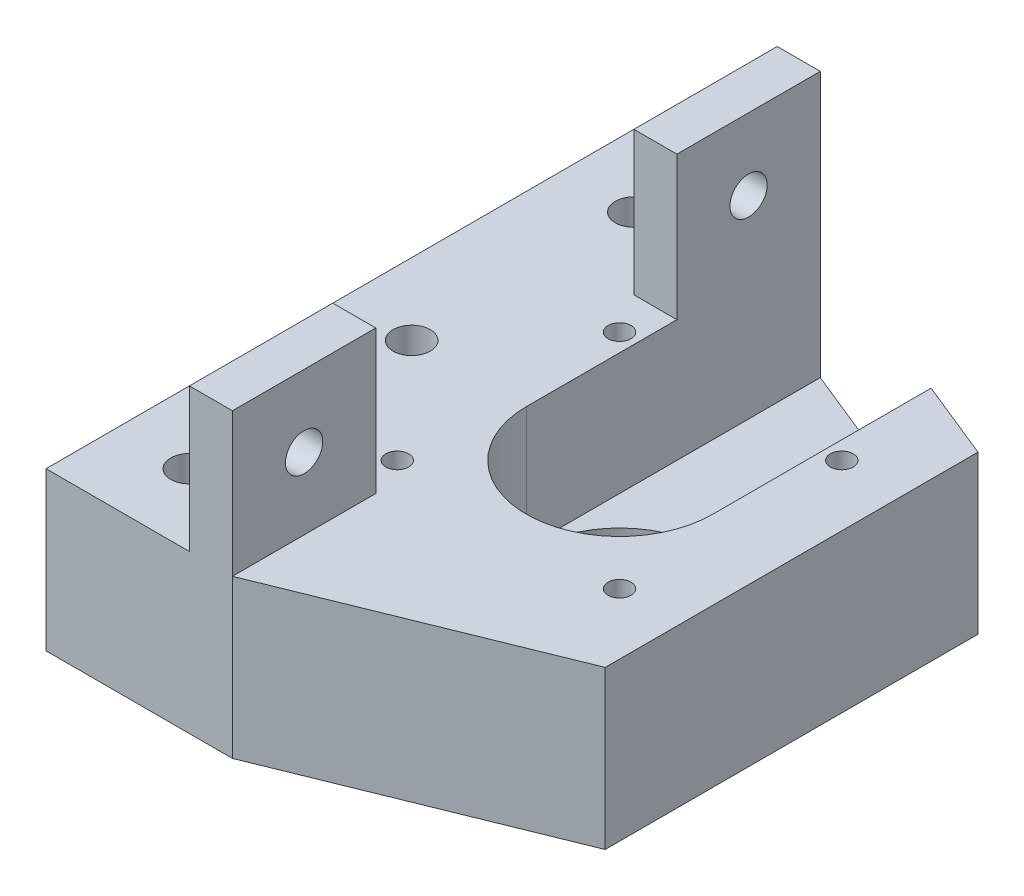
SolidWorks part; units mm, degrees
material "ABS"
ref_plane "Front Plane" through (0, 0, 0) normal (0, 0, 1) x (1, 0, 0)
ref_plane "Top Plane" through (0, 0, 0) normal (0, 1, 0) x (1, 0, 0)
ref_plane "Right Plane" through (0, 0, 0) normal (1, 0, 0) x (0, 0, -1)
sketch "Sketch1" plane through (0, 0, 0) normal (0, 1, 0) x (1, 0, 0)
  line L0 (0, 0) -> (0, 82)
  line L1 (0, 82) -> (26, 82)
  line L2 (26, 82) -> (63, 67)
  line L3 (63, 67) -> (63, 15)
  line L4 (63, 15) -> (26, 0)
  line L5 (26, 0) -> (0, 0)
  line L6 (0, 41) -> (63, 41) construction
  line L7 (26, 82) -> (26, 0) construction
  dimension "D1" = 82
  dimension "D2" = 26
  dimension "D3" = 15
  dimension "D4" = 37
extrude "Boss-Extrude1" add sketch "Sketch1" along normal blind 42
sketch "Sketch2" plane through (0, 0, 0) normal (0, 0, 1) x (1, 0, 0)
  line L0 (0, 42) -> (26, 42) construction
  line L1 (0, 42) -> (20, 42)
  line L2 (0, 42) -> (0, 22)
  line L3 (0, 22) -> (20, 22)
  line L4 (20, 42) -> (20, 22)
  line L5 (0, 42) -> (0, 0) construction
  dimension "D1" = 20
extrude "Cut-Extrude1" cut sketch "Sketch2" against normal through all
sketch "Sketch3" plane through (0, 42, 0) normal (0, 1, 0) x (1, 0, 0)
  line L0 (26, 82) -> (26, 62)
  line L1 (26, 62) -> (20, 62)
  line L2 (20, 82) -> (20, 0) construction
  line L3 (20, 62) -> (20, 20)
  line L4 (20, 20) -> (26, 20)
  line L5 (26, 20) -> (26, 0)
  line L6 (26, 0) -> (63, 15)
  line L7 (63, 15) -> (63, 67)
  line L8 (63, 67) -> (26, 82)
  dimension "D1" = 20
extrude "Cut-Extrude2" cut sketch "Sketch3" against normal offset from surface (37 mm away) 5 up to face at (29.6667, 0, -41)
sketch "Sketch6" plane through (0, 22, 0) normal (0, 1, 0) x (1, 0, 0)
  line L0 (10, 82) -> (10, 72) construction
  line L1 (0, 82) -> (20, 82) construction
  line L2 (10, 72) -> (10, 10) construction
  line L3 (10, 10) -> (10, 0) construction
  line L4 (0, 0) -> (20, 0) construction
  circle A0 centre (10, 72) radius 2.6
  circle A1 centre (10, 41) radius 2.6
  circle A2 centre (10, 10) radius 2.6
  dimension "D1" = 5.2
  dimension "D2" = 10
extrude "Cut-Extrude4" cut sketch "Sketch6" against normal through all
sketch "Sketch5" plane through (20, 0, 0) normal (-1, 0, 0) x (0, 0, 1)
  line L0 (-72, 32) -> (-10, 32) construction
  line L1 (-62, 22) -> (-20, 22) construction
  line L2 (-82, 22) -> (-82, 42) construction
  line L3 (0, 22) -> (0, 42) construction
  circle A0 centre (-72, 32) radius 2.6
  circle A1 centre (-10, 32) radius 2.6
  dimension "D2" = 5.2
  dimension "D1" = 10
  dimension "D3" = 10
  dimension "D4" = 10
extrude "Cut-Extrude3" cut sketch "Sketch5" against normal up to surface (6 mm away) up to face at (26, 23.5, -72)
sketch "Sketch4" plane through (0, 5, 0) normal (0, 1, 0) x (1, 0, 0)
  line L0 (26, 20) -> (63, 20)
  line L1 (63, 15) -> (63, 67) construction
  line L2 (63, 20) -> (63, 15)
  line L3 (63, 15) -> (26, 0)
  line L4 (26, 0) -> (26, 20)
extrude "Boss-Extrude2" add sketch "Sketch4" along normal up to surface (17 mm away) up to face at (10, 22, -7.4)
sketch "Sketch7" plane through (0, 5, 0) normal (0, 1, 0) x (1, 0, 0)
  line L0 (20, 41) -> (63, 41) construction
  line L1 (20, 62) -> (20, 20) construction
  line L2 (63, 20) -> (63, 67) construction
  circle A0 centre (39, 41) radius 12.5
  dimension "D1" = 25
  dimension "D2" = 19
extrude "Cut-Extrude5" cut sketch "Sketch7" against normal through all
sketch "Sketch10" plane through (0, 5, 0) normal (0, 1, 0) x (1, 0, 0)
  line L0 (26, 62) -> (26, 41)
  line L1 (52, 41) -> (52, 71.4595)
  line L2 (63, 67) -> (26, 82) construction
  line L3 (52, 71.4595) -> (63, 67)
  line L4 (63, 67) -> (63, 20)
  line L5 (63, 20) -> (20, 20)
  line L6 (20, 20) -> (20, 62)
  line L7 (20, 62) -> (26, 62)
  arc A0 (26, 41) -> (52, 41) centre (39, 41) ccw
extrude "Boss-Extrude4" add sketch "Sketch10" along normal up to surface (17 mm away) up to face at (10, 22, -7.4)
sketch "Sketch12" plane through (0, 0, 0) normal (0, -1, 0) x (1, 0, 0)
  line L1 (23.5, -56.5) -> (54.5, -56.5) construction
  line L2 (23.5, -56.5) -> (23.5, -25.5) construction
  line L3 (23.5, -25.5) -> (54.5, -25.5) construction
  line L4 (54.5, -56.5) -> (54.5, -25.5) construction
  line L5 (23.5, -56.5) -> (54.5, -25.5) construction
  line L6 (23.5, -25.5) -> (54.5, -56.5) construction
  circle A0 centre (23.5, -25.5) radius 1.6
  circle A1 centre (54.5, -25.5) radius 1.6
  circle A2 centre (54.5, -56.5) radius 1.6
  circle A3 centre (23.5, -56.5) radius 1.6
  point P0 (39, -41)
  dimension "D3" = 3.2
  dimension "D1" = 31
  dimension "D2" = 31
extrude "Cut-Extrude6" cut sketch "Sketch12" against normal through all
